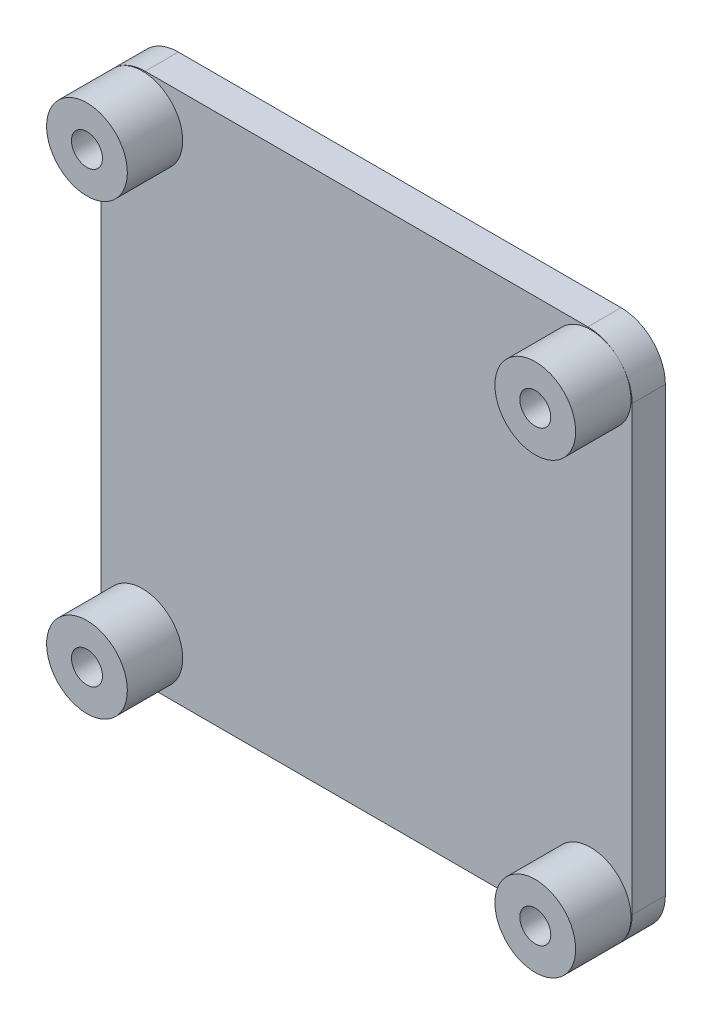
SolidWorks part; units mm, degrees
ref_plane "前视基准面" through (0, 0, 0) normal (0, 0, 1) x (1, 0, 0)
ref_plane "上视基准面" through (0, 0, 0) normal (0, 1, 0) x (1, 0, 0)
ref_plane "右视基准面" through (0, 0, 0) normal (1, 0, 0) x (0, 0, -1)
sketch "草图1" plane through (0, 0, 0) normal (0, 0, 1) x (1, 0, 0)
  line L1 (-24, 24) -> (24, 24)
  line L2 (-24, 24) -> (-24, -24)
  line L3 (-24, -24) -> (24, -24)
  line L4 (24, 24) -> (24, -24)
  line L5 (-24, 24) -> (24, -24) construction
  line L6 (-24, -24) -> (24, 24) construction
  line L7 (-20.25, 20.25) -> (20.25, 20.25) construction
  line L8 (-20.25, 20.25) -> (-20.25, -20.25) construction
  line L9 (-20.25, -20.25) -> (20.25, -20.25) construction
  line L10 (20.25, 20.25) -> (20.25, -20.25) construction
  line L11 (-20.25, 20.25) -> (20.25, -20.25) construction
  line L12 (-20.25, -20.25) -> (20.25, 20.25) construction
  circle A0 centre (-20.25, 20.25) radius 1.4
  circle A1 centre (20.25, 20.25) radius 1.4
  circle A2 centre (20.25, -20.25) radius 1.4
  circle A3 centre (-20.25, -20.25) radius 1.4
  point P0 (0, 0)
  point P5 (0, 0)
  point P21 (0, 0)
  dimension "D5" = 2.8
  dimension "D7" = 20.25
  dimension "D8" = 20.25
  dimension "D1" = 48
  dimension "D2" = 48
  dimension "D3" = 40.5
  dimension "D4" = 40.5
  dimension "D6" = 4
extrude "凸台-拉伸1" add sketch "草图1" along normal blind 3
fillet "圆角1" radius 4 4 edges at (24, -24, 1.5) (-24, 24, 1.5) (24, 24, 1.5) (-24, -24, 1.5)
sketch "草图2" plane through (0, 0, 3) normal (0, 0, 1) x (1, 0, 0)
  circle A1 centre (-20.25, 20.25) radius 3.6464
  circle A2 centre (20.25, 20.25) radius 3.6464
  circle A3 centre (20.25, -20.25) radius 3.6464
  circle A4 centre (-20.25, -20.25) radius 3.6464
  point P13 (0, 0)
  dimension "D2" = 4
extrude "凸台-拉伸2" add sketch "草图2" along normal blind 5
sketch "草图3" plane through (0, 0, 0) normal (0, 0, -1) x (-1, 0, 0)
  circle A0 centre (-20.25, 20.25) radius 1.4
  circle A1 centre (20.25, 20.25) radius 1.4
  circle A2 centre (20.25, -20.25) radius 1.4
  circle A3 centre (-20.25, -20.25) radius 1.4
  point P12 (0, 0)
  dimension "D1" = 4
extrude "切除-拉伸1" cut sketch "草图3" against normal blind 99
